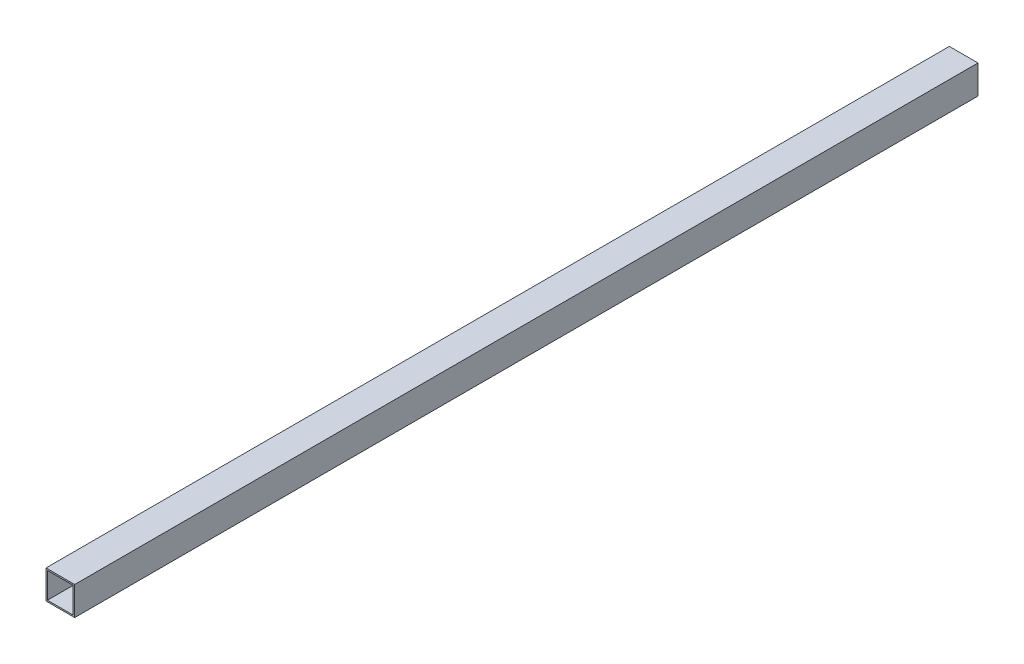
SolidWorks part; units mm, degrees
ref_plane "Front Plane" through (0, 0, 0) normal (0, 0, 1) x (1, 0, 0)
ref_plane "Top Plane" through (0, 0, 0) normal (0, 1, 0) x (1, 0, 0)
ref_plane "Right Plane" through (0, 0, 0) normal (1, 0, 0) x (0, 0, -1)
sketch "Sketch1" plane through (0, 0, 0) normal (0, 0, 1) x (1, 0, 0)
  line L5 (-15.875, 15.875) -> (15.875, 15.875)
  line L6 (-15.875, 15.875) -> (-15.875, -15.875)
  line L11 (-15.875, -15.875) -> (15.875, -15.875)
  line L12 (15.875, 15.875) -> (15.875, -15.875)
  line L13 (-15.875, 15.875) -> (15.875, -15.875) construction
  line L14 (-15.875, -15.875) -> (15.875, 15.875) construction
  line L15 (-14.2875, 14.2875) -> (14.2875, 14.2875)
  line L16 (-14.2875, 14.2875) -> (-14.2875, -14.2875)
  line L17 (-14.2875, -14.2875) -> (14.2875, -14.2875)
  line L18 (14.2875, 14.2875) -> (14.2875, -14.2875)
  line L19 (-14.2875, 14.2875) -> (14.2875, -14.2875) construction
  line L20 (-14.2875, -14.2875) -> (14.2875, 14.2875) construction
  point P0 (0, 0)
  point P6 (0, 0)
  dimension "D1" = 31.75
  dimension "D2" = 31.75
  dimension "D3" = 1.5875
extrude "Boss-Extrude1" add sketch "Sketch1" along normal blind 1000
